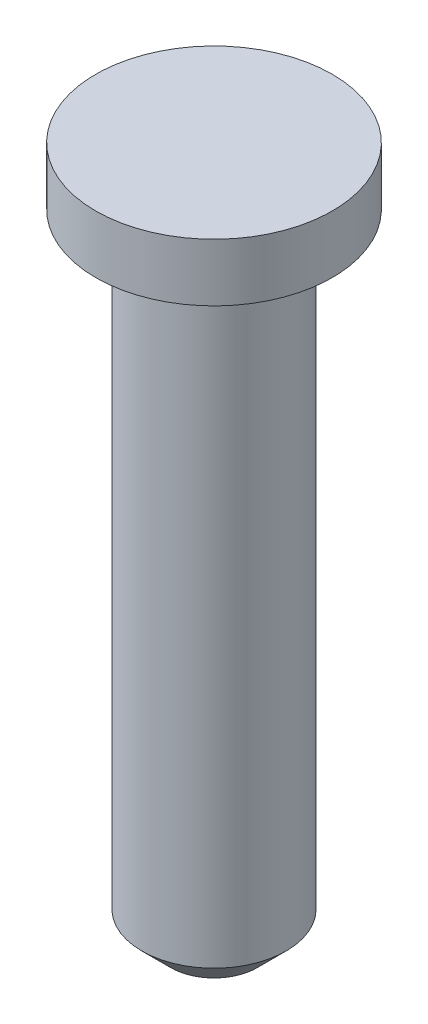
SolidWorks part; units mm, degrees
material "acero"
ref_plane "Alzado" through (0, 0, 0) normal (0, 0, 1) x (1, 0, 0)
ref_plane "Planta" through (0, 0, 0) normal (0, 1, 0) x (1, 0, 0)
ref_plane "Vista lateral" through (0, 0, 0) normal (1, 0, 0) x (0, 0, -1)
sketch "Croquis1" plane through (0, 0, 0) normal (0, 0, 1) x (1, 0, 0)
  line L0 (0, 0) -> (0, -60.9498) construction
  line L1 (0, 0) -> (2.05, 0)
  line L2 (2.05, 0) -> (2.05, -1)
  line L3 (2.05, -1) -> (1.25, -1)
  line L4 (1.25, -1) -> (1.25, -12)
  line L5 (1.25, -12) -> (0, -12)
  line L6 (0, -12) -> (0, 0)
  dimension "D1" = 12
  dimension "D2" = 1
  dimension "D3" = 4.1
  dimension "D4" = 2.5
revolve "Revolución1" add sketch "Croquis1" angle 360 about L0
chamfer "Chaflán1" distance 0.5 angle 45 1 edges at (0, -12, 1.25)
